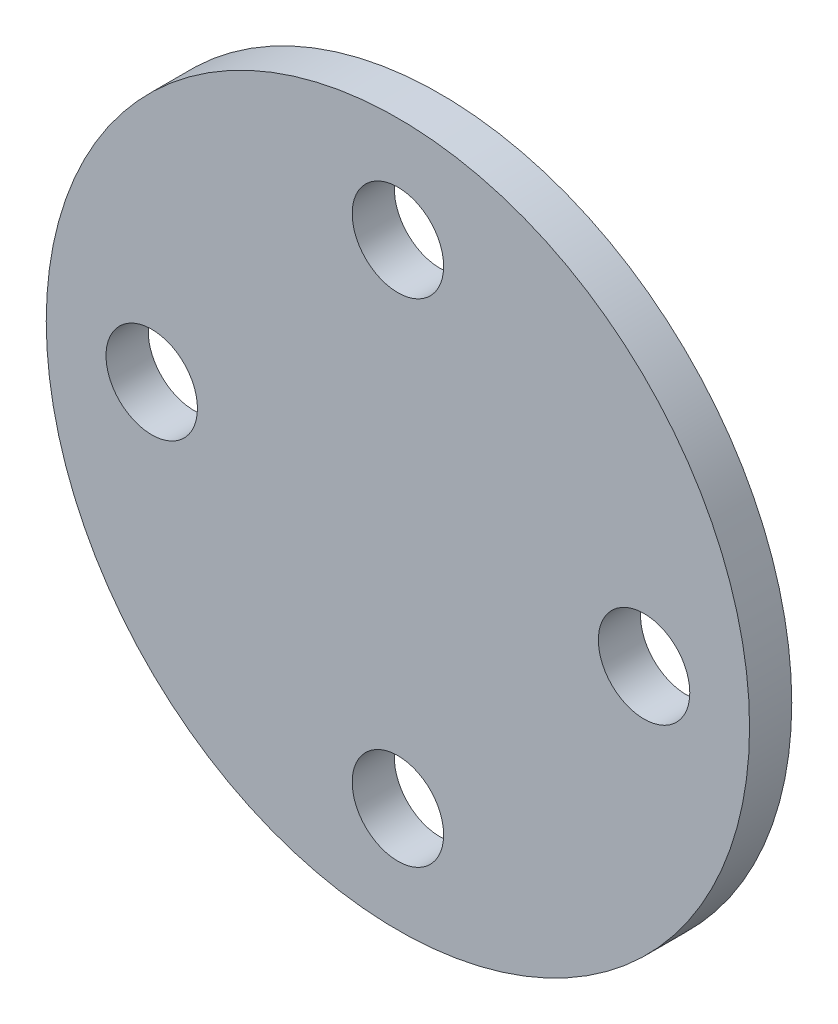
SolidWorks part; units mm, degrees
ref_plane "Alzado" through (0, 0, 0) normal (0, 0, 1) x (1, 0, 0)
ref_plane "Planta" through (0, 0, 0) normal (0, 1, 0) x (1, 0, 0)
ref_plane "Vista lateral" through (0, 0, 0) normal (1, 0, 0) x (0, 0, -1)
sketch "Sketch1" plane through (0, 0, 0) normal (0, 0, 1) x (1, 0, 0)
  circle A0 centre (0, 0) radius 25
  circle A1 centre (0, 0) radius 17.5 construction
  circle A2 centre (0, 17.5) radius 3.25
  circle A3 centre (17.5, 0) radius 3.25
  circle A4 centre (0, -17.5) radius 3.25
  circle A5 centre (-17.5, 0) radius 3.25
  point P15 (0, 0)
  dimension "D1" = 50
  dimension "D2" = 35
  dimension "D3" = 6.5
  dimension "D4" = 4
extrude "Boss-Extrude2" add sketch "Sketch1" along normal blind 3
